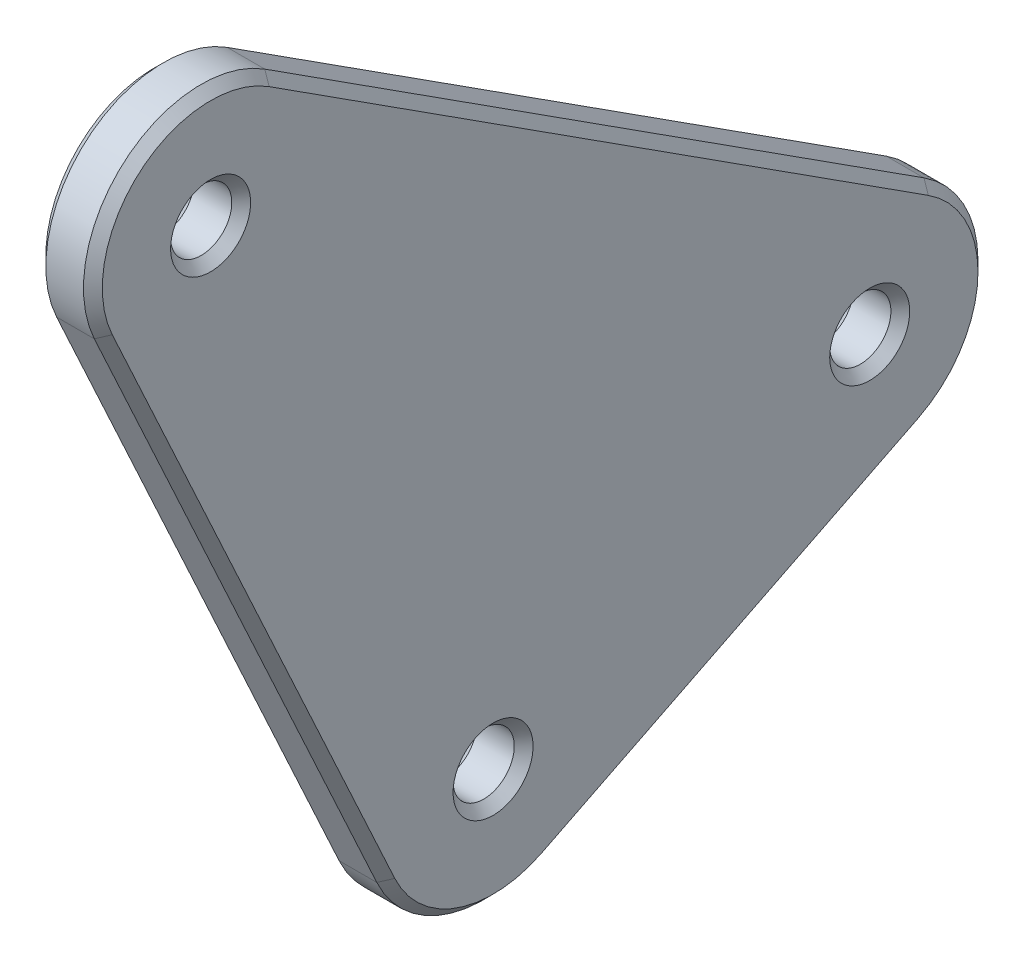
SolidWorks part; units mm, degrees
ref_plane "前视基准面" through (0, 0, 0) normal (0, 0, 1) x (1, 0, 0)
ref_plane "上视基准面" through (0, 0, 0) normal (0, 1, 0) x (1, 0, 0)
ref_plane "右视基准面" through (0, 0, 0) normal (1, 0, 0) x (0, 0, -1)
ref_plane "基准面1" through (-1.5, 0, 0) normal (-1, 0, 0) x (0, -1, 0)
sketch "草图1" plane through (-1.5, 0, 0) normal (-1, 0, 0) x (0, -1, 0)
  line L0 (-4.4098, -22.7951) -> (5.5902, -2.7951)
  line L1 (2.6191, 5.6747) -> (-29.8809, 20.6747)
  line L2 (-37.7574, 11.6203) -> (-15.2574, -23.3797)
  line L3 (-25.6962, 9.5018) -> (-12.1773, -11.5276)
  line L4 (-15.1214, -13.4203) -> (-28.6404, 7.6092)
  line L5 (-15.542, 7.1135) -> (-6.0787, -7.6072)
  line L6 (-9.0229, -9.4998) -> (-18.4861, 5.2208)
  circle A0 centre (0, 0) radius 1.625
  circle A1 centre (-32.5, 15) radius 1.625
  arc A2 (5.5902, -2.7951) -> (2.6191, 5.6747) centre (0, 0) ccw
  arc A3 (-29.8809, 20.6747) -> (-37.7574, 11.6203) centre (-32.5, 15) ccw
  arc A4 (-15.2574, -23.3797) -> (-4.4098, -22.7951) centre (-10, -20) ccw
  circle A5 centre (-10, -20) radius 1.625
  arc A6 (-28.6404, 7.6092) -> (-25.6962, 9.5018) centre (-27.1683, 8.5555) cw
  arc A7 (-12.1773, -11.5276) -> (-15.1214, -13.4203) centre (-13.6494, -12.474) cw
  arc A8 (-6.0787, -7.6072) -> (-9.0229, -9.4998) centre (-7.5508, -8.5535) cw
  arc A9 (-18.4861, 5.2208) -> (-15.542, 7.1135) centre (-17.0141, 6.1671) cw
  dimension "D1" = 6.25
  dimension "D2" = 1.75
  dimension "D3" = 3.25
  dimension "D4" = 3.25
  dimension "D8" = 6.25
  dimension "D9" = 6.25
  dimension "D5" = 41.6083
  dimension "D6" = 35.7946
  dimension "D7" = 22.3607
  dimension "D10" = 17.5
  dimension "D11" = 25
extrude "凸台-拉伸1" add sketch "草图1" against normal blind 3
chamfer "倒角1" distance 0.5 angle 45 34 edges at (-1.5, 26.5074, -5.8797) (-1.5, 37.2155, 19.102) (-1.5, 13.6309, 13.1747) (-1.5, -5.8977, 2.0688) (-1.5, -0.5902, -12.7951) (-1.5, 9.6636, -26.2409) (-1.5, 0, -1.625) (-1.5, 32.5, 13.375) (-1.5, 10, -21.625) (-1.5, 21.8809, -2.9056) (-1.5, 12.703, -13.946) (-1.5, 18.9368, -1.0129) (-1.5, 28.1146, 10.0276) (-1.5, 13.7545, -2.1395) (-1.5, 6.6045, -10.0255) (-1.5, 10.8104, -0.2468) (-1.5, 17.9604, 7.6392) (1.5, -0.5902, -12.7951) (1.5, -5.8977, 2.0688) (1.5, 13.6309, 13.1747) (1.5, 37.2155, 19.102) (1.5, 26.5074, -5.8797) (1.5, 9.6636, -26.2409) (1.5, 0, -1.625) (1.5, 32.5, 13.375) (1.5, 10, -21.625) (1.5, 12.703, -13.946) (1.5, 21.8809, -2.9056) (1.5, 28.1146, 10.0276) (1.5, 18.9368, -1.0129) (1.5, 6.6045, -10.0255) (1.5, 13.7545, -2.1395) (1.5, 17.9604, 7.6392) (1.5, 10.8104, -0.2468)
ref_plane "基准面2" through (1.5, 0, 0) normal (1, 0, 0) x (0, 0, -1)
sketch "草图2" plane through (1.5, 0, 0) normal (1, 0, 0) x (0, 0, -1)
  line L0 (-11.7505, 30.9251) -> (-5.0786, 2.5588)
  line L3 (-3.928, 10.8059) -> (0.2779, 8.1021)
  line L4 (-5.8207, 7.8618) -> (-1.6148, 5.158)
  arc A0 (-4.9504, 18.9067) -> (-7.3838, 15.1214) centre (-6.1671, 17.0141) ccw construction
  arc A1 (-7.3388, 29.0609) -> (-9.7722, 25.2756) centre (-8.5555, 27.1683) ccw construction
  arc A2 (-4.9504, 18.9067) -> (-7.3838, 15.1214) centre (-6.1671, 17.0141) ccw
  arc A3 (-7.3388, 29.0609) -> (-9.7722, 25.2756) centre (-8.5555, 27.1683) ccw
  arc A4 (-3.928, 10.8059) -> (-5.8207, 7.8618) centre (-4.8743, 9.3338) ccw
  arc A5 (-1.6148, 5.158) -> (0.2779, 8.1021) centre (-0.6684, 6.63) ccw
  dimension "D1" = 3.5
  dimension "D2" = 3.5
  dimension "D3" = 5
extrude "切除-拉伸1" cut sketch "草图2" against normal blind 10
chamfer "倒角2" distance 0.5 angle 45 8 edges at (-1.5, 6.5099, 3.7177) (-1.5, 5.6837, -0.8036) (-1.5, 10.2802, 6.3464) (-1.5, 9.454, 1.8251) (1.5, 6.5099, 3.7177) (1.5, 10.2802, 6.3464) (1.5, 5.6837, -0.8036) (1.5, 9.454, 1.8251)
sketch3d "3D草图1"
  line L0 (1.5, 33.431, 9.7798) -> (1.5, 16.8284, -16.3079)
  line L1 (1.5, 16.8284, -16.3079) -> (1.5, 9.8866, -16.3079)
  line L2 (1.5, 9.8866, -16.3079) -> (1.5, 1.4883, -8.4971)
  line L3 (1.5, 1.4883, -8.4971) -> (1.5, 2.7209, -1.2065)
  line L4 (1.5, 2.7209, -1.2065) -> (1.5, 5.3975, 6.4126)
  line L5 (1.5, 5.3975, 6.4126) -> (1.5, 14.1147, 11.0272)
  line L6 (1.5, 14.1147, 11.0272) -> (1.5, 28.9647, 11.7748)
  line L7 (1.5, 28.9647, 11.7748) -> (1.5, 33.431, 9.7798)
extrude "凸台-拉伸2" add sketch "3D草图1" along direction (-1, 0, 0) on the side against the normal blind 3
